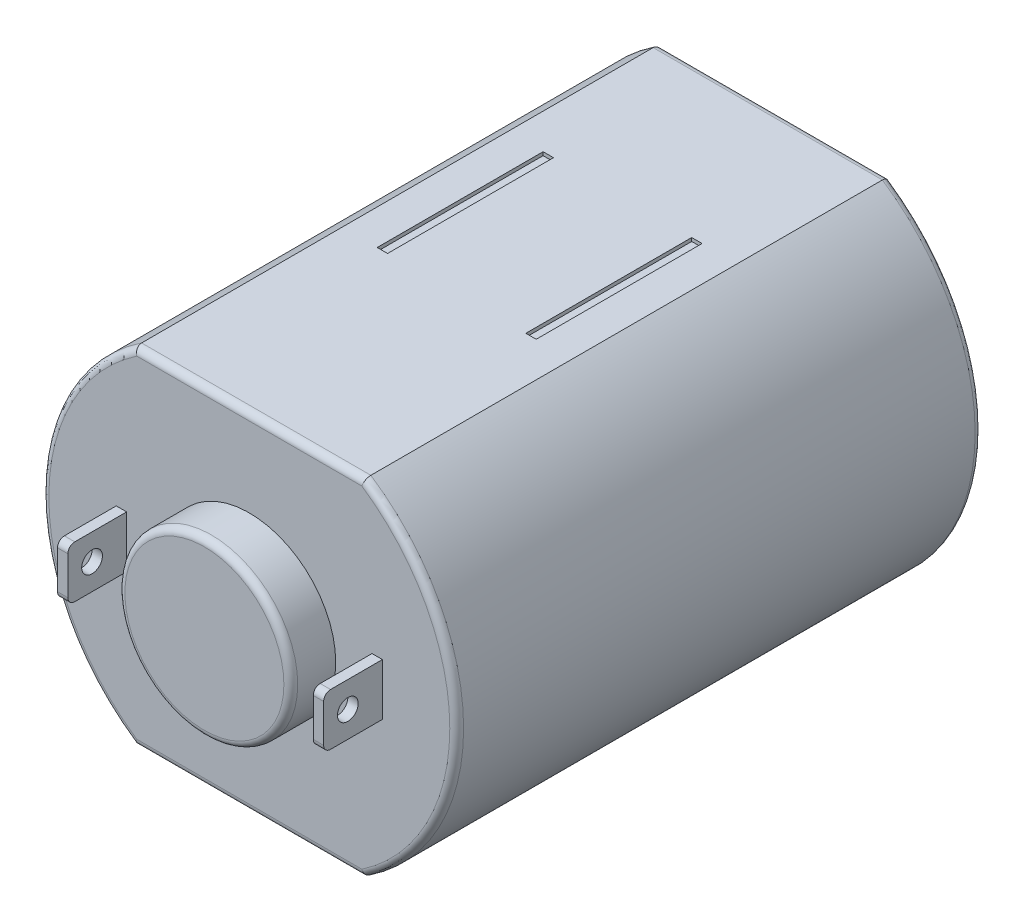
SolidWorks part; units mm, degrees
ref_plane "Ebene vorne" through (0, 0, 0) normal (0, 0, 1) x (1, 0, 0)
ref_plane "Ebene oben" through (0, 0, 0) normal (0, 1, 0) x (1, 0, 0)
ref_plane "Ebene rechts" through (0, 0, 0) normal (1, 0, 0) x (0, 0, -1)
sketch "Skizze1" plane through (0, 0, 0) normal (0, 0, 1) x (1, 0, 0)
  line L1 (-3.3166, 5) -> (3.3166, 5)
  line L3 (-3.3166, -5) -> (3.3166, -5)
  line L5 (-6, 5) -> (6, -5) construction
  line L6 (-6, -5) -> (6, 5) construction
  arc A0 (-3.3166, 5) -> (-3.3166, -5) centre (0, 0) ccw
  arc A1 (3.3166, -5) -> (3.3166, 5) centre (0, 0) ccw
  point P0 (0, 0)
  dimension "D3" = 12
  dimension "D1" = 10
  dimension "D2" = 12
extrude "Aufsatz-Linear austragen1" add sketch "Skizze1" along normal blind 15.2
sketch "Skizze2" plane through (0, 0, 15.2) normal (0, 0, 1) x (1, 0, 0)
  circle A0 centre (0, 0) radius 2.5
  dimension "D1" = 5
extrude "Aufsatz-Linear austragen2" add sketch "Skizze2" along normal blind 1.3
sketch "Skizze3" plane through (0, 0, 0) normal (0, 0, -1) x (-1, 0, 0)
  circle A0 centre (0, 0) radius 0.5
  dimension "D1" = 1
extrude "Aufsatz-Linear austragen3" add sketch "Skizze3" along normal blind 2
fillet "Verrundung1" radius 0.2 9 edges at (2.5, 0, 16.5) (0, 5, 15.2) (6, 0, 15.2) (0, -5, 15.2) (-6, 0, 15.2) (0, -5, 0) (-6, 0, 0) (0, 5, 0) (6, 0, 0)
sketch "Skizze4" plane through (0, 5, 0) normal (0, 1, 0) x (1, 0, 0)
  line L0 (0, 0) -> (0, -15) construction
  line L1 (-2.3, -4.4) -> (-2, -4.4)
  line L2 (-2.3, -4.4) -> (-2.3, -9.2)
  line L3 (-2.3, -9.2) -> (-2, -9.2)
  line L4 (-2, -4.4) -> (-2, -9.2)
  line L5 (-3.3166, -15) -> (3.3166, -15) construction
  line L6 (3.2558, -15.2) -> (-3.2558, -15.2) construction
  line L7 (2, -4.4) -> (2, -9.2)
  line L8 (2.3, -9.2) -> (2, -9.2)
  line L9 (2.3, -4.4) -> (2.3, -9.2)
  line L10 (2.3, -4.4) -> (2, -4.4)
  dimension "D1" = 6
  dimension "D2" = 4.8
  dimension "D3" = 0.3
  dimension "D4" = 4
extrude "Schnitt-Linear austragen1" cut sketch "Skizze4" against normal blind 0.1
ref_plane "Ebene1" through (0, 0, 0) normal (0, 1, 0) x (1, 0, 0)
mirror "Spiegeln1" about plane through (0, 0, 0) normal (0, 1, 0) of "Schnitt-Linear austragen1"
sketch "Skizze5" plane through (0, 0, 15.2) normal (0, 0, 1) x (1, 0, 0)
  line L0 (-3.7, 0) -> (3.7, 0) construction
  line L1 (-3.55, 0.75) -> (-3.85, 0.75)
  line L2 (-3.55, 0.75) -> (-3.55, -0.75)
  line L3 (-3.55, -0.75) -> (-3.85, -0.75)
  line L4 (-3.85, 0.75) -> (-3.85, -0.75)
  line L5 (-3.55, 0.75) -> (-3.85, -0.75) construction
  line L6 (-3.55, -0.75) -> (-3.85, 0.75) construction
  line L7 (3.6483, 0) -> (-3.6483, 0) construction
  line L8 (0, 0) -> (0, 3.7895) construction
  line L9 (3.55, -0.75) -> (3.85, 0.75) construction
  line L10 (3.55, 0.75) -> (3.85, -0.75) construction
  line L11 (3.85, 0.75) -> (3.85, -0.75)
  line L12 (3.55, -0.75) -> (3.85, -0.75)
  line L13 (3.55, 0.75) -> (3.55, -0.75)
  line L14 (3.55, 0.75) -> (3.85, 0.75)
  point P0 (-3.7, 0)
  dimension "D1" = 0.3
  dimension "D2" = 1.5
  dimension "D3" = 7.4
extrude "Aufsatz-Linear austragen4" add sketch "Skizze5" along normal blind 1.7
sketch "Skizze6" plane through (-3.85, 0, 0) normal (-1, 0, 0) x (0, 0, 1)
  line L0 (16.9, 0.75) -> (16.9, -0.75) construction
  circle A0 centre (16.2, 0) radius 0.3
  dimension "D1" = 0.6
  dimension "D2" = 0.7
extrude "Schnitt-Linear austragen2" cut sketch "Skizze6" against normal up to next
mirror "Spiegeln6" about plane through (0, 0, 0) normal (1, 0, 0) of "Schnitt-Linear austragen2"
fillet "Verrundung2" radius 0.2 4 edges at (-3.7, 0.75, 16.9) (-3.7, -0.75, 16.9) (3.7, -0.75, 16.9) (3.7, 0.75, 16.9)
